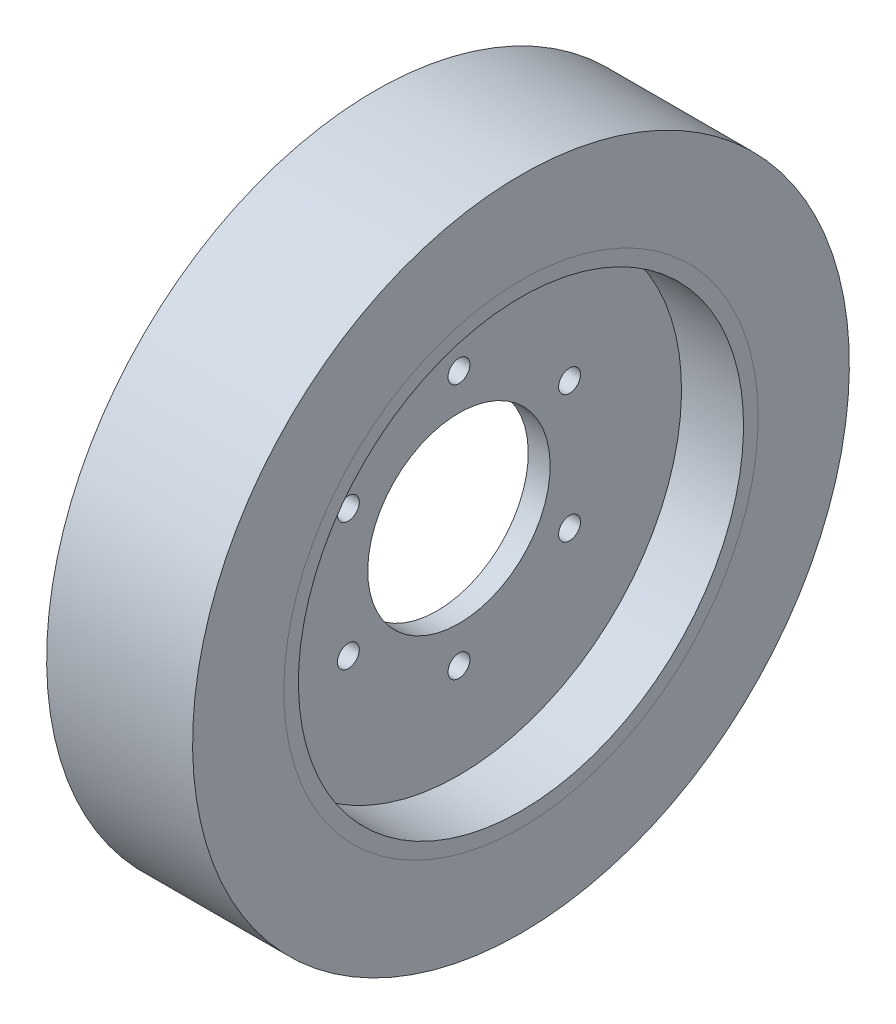
SolidWorks part; units mm, degrees
material "1060 Alloy"
ref_plane "Front Plane" through (0, 0, 0) normal (0, 0, 1) x (1, 0, 0)
ref_plane "Top Plane" through (0, 0, 0) normal (0, 1, 0) x (1, 0, 0)
ref_plane "Right Plane" through (0, 0, 0) normal (1, 0, 0) x (0, 0, -1)
sketch "Sketch1" plane through (0, 0, 0) normal (0, 0, 1) x (1, 0, 0)
  line L0 (0, 0) -> (0, 65) construction
  line L1 (0, 65) -> (-20, 65)
  line L2 (-20, 65) -> (-20, 59)
  line L3 (-20, 59) -> (-3, 59)
  line L4 (-3, 59) -> (-3, 0)
  line L5 (0, 0) -> (-3, 0) construction
  line L6 (0, 65) -> (20, 65)
  line L7 (20, 65) -> (20, 61)
  line L8 (20, 61) -> (3, 61)
  line L9 (3, 61) -> (3, 0)
  line L10 (0, 0) -> (3, 0) construction
  line L11 (-3, 0) -> (3, 0)
  dimension "D1" = 118
  dimension "D2" = 40
  dimension "D3" = 6
  dimension "D4" = 6
  dimension "D5" = 122
revolve "Revolve1" add sketch "Sketch1" angle 360 about L11
sketch "Sketch2" plane through (-3, 0, 0) normal (-1, 0, 0) x (0, 0, 1)
  line L0 (0, 0) -> (0, 35) construction
  circle A0 centre (0, 0) radius 25
  circle A1 centre (0, 35) radius 3
  circle A2 centre (30.3109, 17.5) radius 3
  circle A3 centre (30.3109, -17.5) radius 3
  circle A4 centre (0, -35) radius 3
  circle A5 centre (-30.3109, -17.5) radius 3
  circle A6 centre (-30.3109, 17.5) radius 3
  point P17 (0, 0)
  dimension "D1" = 50
  dimension "D3" = 6
  dimension "D2" = 35
  dimension "D4" = 6
extrude "Cut-Extrude1" cut sketch "Sketch2" against normal through all
sketch "Sketch4" plane through (-20, 0, 0) normal (-1, 0, 0) x (0, 0, 1)
  circle A0 centre (0, 0) radius 65
  circle A1 centre (0, 0) radius 90
  circle A2 centre (0, 0) radius 65 construction
  dimension "D1" = 180
extrude "Boss-Extrude1" add sketch "Sketch4" against normal up to surface (40 mm away) separate body up to face at (20, -65, 0)
